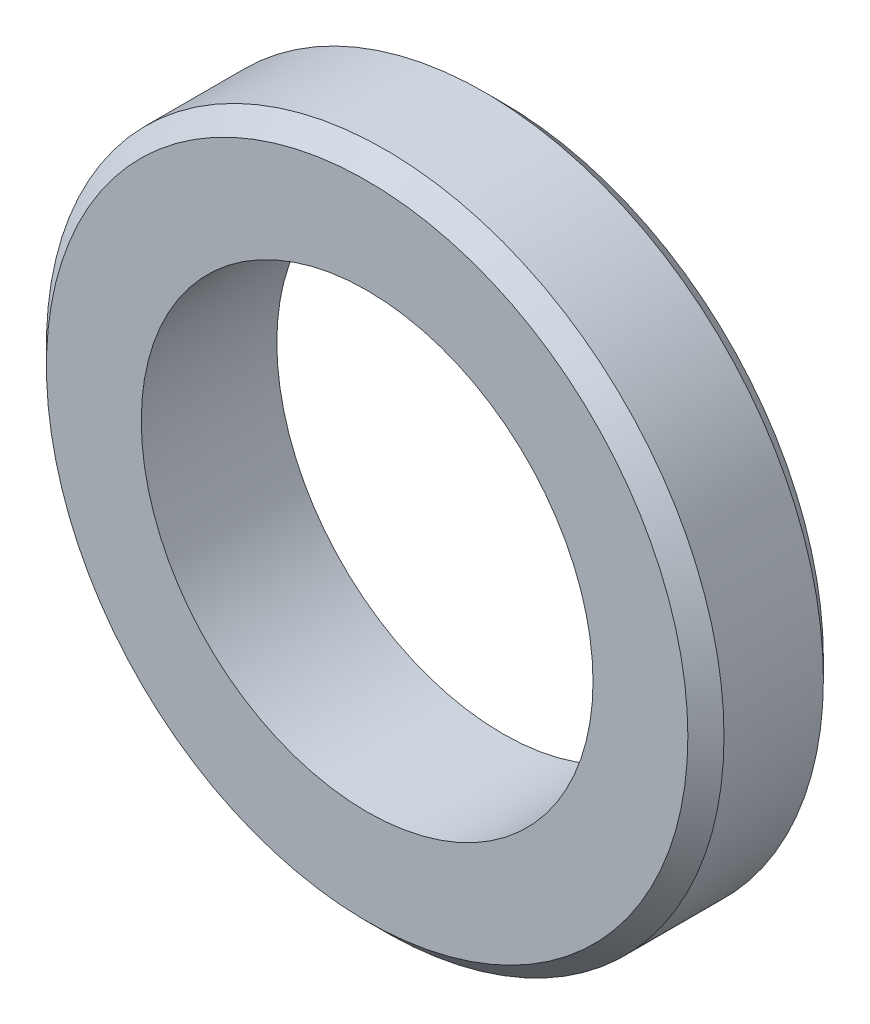
SolidWorks part; units mm, degrees
material "1023 Carbon Steel Sheet (SS)"
ref_plane "Front Plane" through (0, 0, 0) normal (0, 0, 1) x (1, 0, 0)
ref_plane "Top Plane" through (0, 0, 0) normal (0, 1, 0) x (1, 0, 0)
ref_plane "Right Plane" through (0, 0, 0) normal (1, 0, 0) x (0, 0, -1)
sketch "Sketch1" plane through (0, 0, 0) normal (0, 0, 1) x (1, 0, 0)
  circle A0 centre (0, 0) radius 5
  circle A1 centre (0, 0) radius 7.5
  dimension "D1" = 10
  dimension "D2" = 15
extrude "Boss-Extrude1" add sketch "Sketch1" along normal blind 3
chamfer "Chamfer1" distance 0.4 angle 45 2 edges at (7.5, 0, 0) (7.5, 0, 3)
